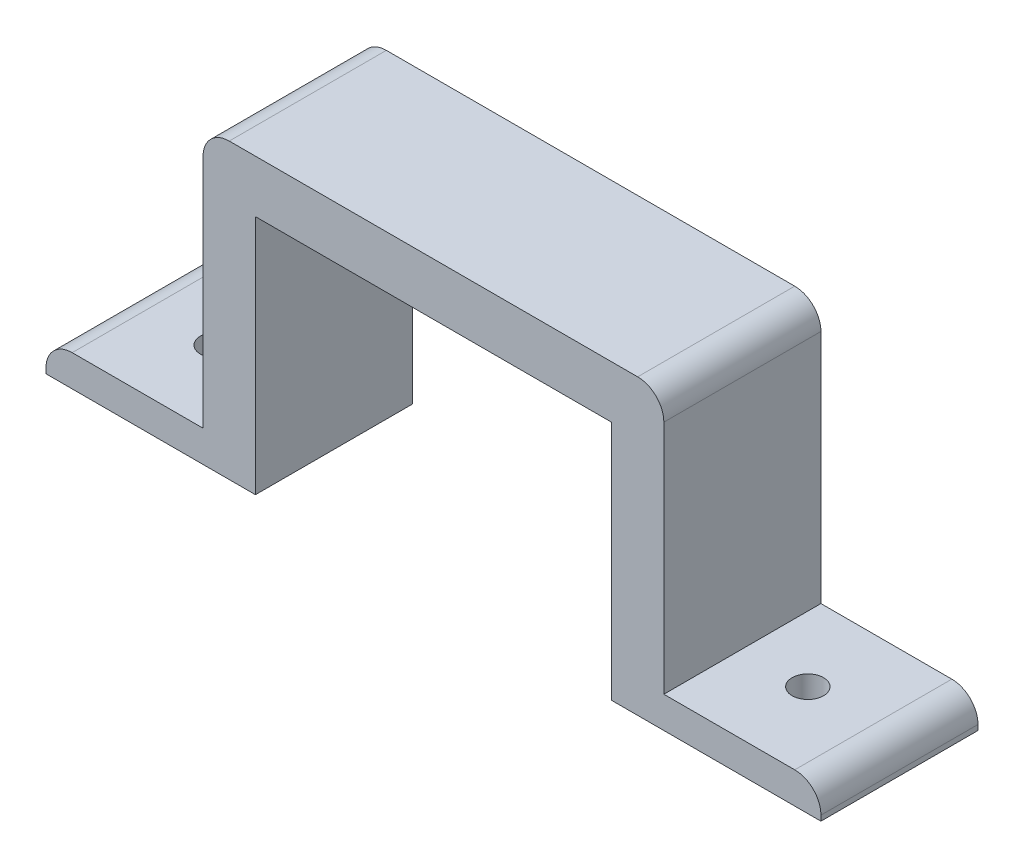
SolidWorks part; units mm, degrees
ref_plane "Front Plane" through (0, 0, 0) normal (0, 0, 1) x (1, 0, 0)
ref_plane "Top Plane" through (0, 0, 0) normal (0, 1, 0) x (1, 0, 0)
ref_plane "Right Plane" through (0, 0, 0) normal (1, 0, 0) x (0, 0, -1)
sketch "Sketch1" plane through (0, 0, 0) normal (0, 0, 1) x (1, 0, 0)
  line L0 (0, 0) -> (0, 23) construction
  line L1 (17, 23) -> (-17, 23)
  line L2 (-17, 23) -> (-17, 0)
  line L3 (-17, 0) -> (-37, 0)
  line L4 (-37, 0) -> (-37, 3)
  line L5 (-37, 3) -> (-22, 3)
  line L6 (-22, 3) -> (-22, 28)
  line L7 (-22, 28) -> (22, 28)
  line L8 (22, 3) -> (22, 28)
  line L9 (37, 3) -> (22, 3)
  line L10 (37, 0) -> (37, 3)
  line L11 (17, 23) -> (17, 0)
  line L12 (17, 0) -> (37, 0)
  point P12 (0, 28)
  dimension "D1" = 28
  dimension "D2" = 23
  dimension "D3" = 3
  dimension "D4" = 17
  dimension "D5" = 22
  dimension "D6" = 37
extrude "Boss-Extrude1" add sketch "Sketch1" along normal blind 15
fillet "Fillet1" radius 2.5 4 edges at (-37, 3, 7.5) (-22, 28, 7.5) (22, 28, 7.5) (37, 3, 7.5)
sketch "Sketch2" plane through (0, 3, 0) normal (0, 1, 0) x (1, 0, 0)
  line L0 (-28.25, 0) -> (-28.25, -15) construction
  line L1 (-22, 0) -> (-34.5, 0) construction
  line L2 (-22, -15) -> (-34.5, -15) construction
  line L3 (0, 0) -> (0, -15) construction
  line L4 (19.5, -15) -> (-19.5, -15) construction
  circle A0 centre (-28.25, -7.5) radius 1.5
  circle A1 centre (28.25, -7.5) radius 1.5
  dimension "D1" = 3
extrude "Cut-Extrude1" cut sketch "Sketch2" against normal up to surface (3 mm away) up to face at (-27, 0, 7.5)
